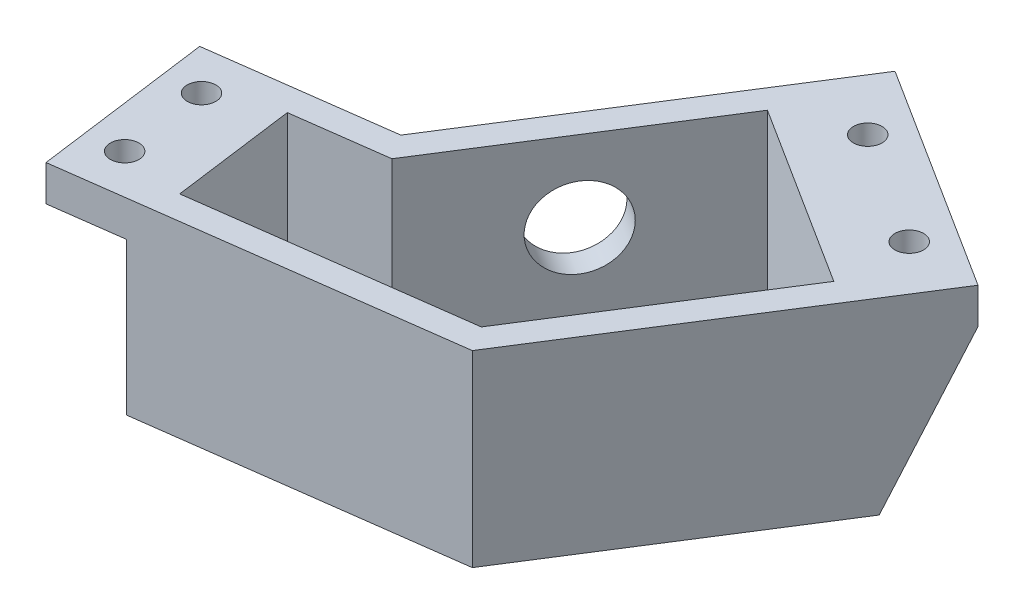
SolidWorks part; units mm, degrees
ref_plane "Спереди" through (0, 0, 0) normal (0, 0, 1) x (1, 0, 0)
ref_plane "Сверху" through (0, 0, 0) normal (0, 1, 0) x (1, 0, 0)
ref_plane "Справа" through (0, 0, 0) normal (1, 0, 0) x (0, 0, -1)
sketch "Sketch1" plane through (0, 0, 0) normal (0, 1, 0) x (1, 0, 0)
  line L0 (0, 0) -> (-19.8234, -2.6518)
  line L1 (-19.8234, -2.6518) -> (-17.1716, -22.4752)
  line L2 (-17.1716, -22.4752) -> (24.8344, -16.856)
  line L3 (24.8344, -16.856) -> (46.7569, 17.7141)
  line L4 (46.7569, 17.7141) -> (21.4217, 33.7803)
  line L5 (21.4217, 33.7803) -> (0, 0)
  line L6 (0, 0) -> (2.6518, -19.8234) construction
  dimension "D1" = 130
  dimension "D2" = 20
  dimension "D3" = 20
  dimension "D4" = 30
  dimension "D5" = 90
  dimension "D6" = 40
extrude "Boss-Extrude1" add sketch "Sketch1" along normal blind 21
sketch "Sketch2" plane through (0, 21, 0) normal (0, 1, 0) x (1, 0, 0)
  line L0 (21.4217, 33.7803) -> (17.1373, 27.0243)
  line L1 (21.4217, 33.7803) -> (0, 0) construction
  line L2 (17.1373, 27.0243) -> (42.4726, 10.958)
  line L3 (24.8344, -16.856) -> (46.7569, 17.7141) construction
  line L4 (42.4726, 10.958) -> (46.7569, 17.7141)
  line L5 (46.7569, 17.7141) -> (21.4217, 33.7803)
  line L6 (-19.8234, -2.6518) -> (-17.1716, -22.4752)
  line L7 (-17.1716, -22.4752) -> (-9.2422, -21.4145)
  line L8 (-17.1716, -22.4752) -> (24.8344, -16.856) construction
  line L9 (-9.2422, -21.4145) -> (-11.8941, -1.5911)
  line L10 (0, 0) -> (-19.8234, -2.6518) construction
  line L11 (-11.8941, -1.5911) -> (-19.8234, -2.6518)
  dimension "D1" = 8
extrude "Cut-Extrude1" cut sketch "Sketch2" along normal offset from surface (17 mm away) 4 from surface at -21 up to face at (9.3363, 21, -1.5852) starting at face at (9.3363, 0, -1.5852)
sketch "Sketch3" plane through (0, 21, 0) normal (0, 1, 0) x (1, 0, 0)
  line L0 (18.0642, 22.8841) -> (1.7843, -2.788)
  line L1 (1.7843, -2.788) -> (-8.5228, -4.1668)
  line L2 (-8.5228, -4.1668) -> (-6.6665, -18.0432)
  line L3 (-6.6665, -18.0432) -> (23.0501, -14.068)
  line L4 (23.0501, -14.068) -> (38.3324, 10.0311)
  line L5 (38.3324, 10.0311) -> (18.0642, 22.8841)
  line L6 (18.0642, 22.8841) -> (17.864, 23.073)
  line L7 (21.4217, 33.7803) -> (0, 0) construction
  line L9 (0, 0) -> (-19.8234, -2.6518) construction
  line L10 (-9.2422, -21.4145) -> (-11.8941, -1.5911) construction
  line L11 (-17.1716, -22.4752) -> (24.8344, -16.856) construction
  line L12 (24.8344, -16.856) -> (46.7569, 17.7141) construction
  line L13 (17.1373, 27.0243) -> (42.4726, 10.958) construction
  dimension "D1" = 3
  dimension "D2" = 3
  dimension "D3" = 3
  dimension "D4" = 3
  dimension "D5" = 3
  dimension "D6" = 3
extrude "Cut-Extrude2" cut sketch "Sketch3" against normal offset from surface (18 mm away) 3 contours L4 L5 L0 L1 L2 L3 up to face at (10.5514, 0, 0.3132)
sketch "Sketch4" plane through (2.5335, 0, 1.6066) normal (0.8445, 0, 0.5355) x (0.5355, 0, -0.8445)
  line L0 (13.8005, 3) -> (13.8005, 21) construction
  line L3 (29, 21) -> (-1.3989, 21) construction
  line L4 (3.3005, 4) -> (24.3005, 4) construction
  line L5 (3.3005, 4) -> (3.3005, 20) construction
  line L6 (3.3005, 20) -> (24.3005, 20) construction
  line L7 (24.3005, 4) -> (24.3005, 20) construction
  line L8 (3.3005, 4) -> (24.3005, 20) construction
  line L9 (3.3005, 20) -> (24.3005, 4) construction
  line L11 (29, 3) -> (-1.3989, 3) construction
  circle A0 centre (13.8005, 12) radius 4.5
  point P14 (13.8005, 21)
  dimension "D1" = 9
  dimension "D2" = 16
  dimension "D3" = 21
extrude "Cut-Extrude3" cut sketch "Sketch4" against normal through all
sketch "Sketch5" plane through (0, 17, 0) normal (0, -1, 0) x (-1, 0, 0)
  line L0 (-19.2795, 30.4023) -> (-44.6148, 14.3361) construction
  line L1 (-21.4217, 33.7803) -> (-17.1373, 27.0243) construction
  line L2 (-42.4726, 10.958) -> (-46.7569, 17.7141) construction
  line L3 (15.8587, -2.1215) -> (13.2069, -21.9449) construction
  line L4 (11.8941, -1.5911) -> (19.8234, -2.6518) construction
  line L5 (17.1716, -22.4752) -> (9.2422, -21.4145) construction
  line L8 (-21.4217, 33.7803) -> (-17.1373, 27.0243) construction
  circle A0 centre (-38.7032, 18.0848) radius 1.6
  circle A1 centre (-26.0356, 26.118) radius 1.6
  circle A2 centre (13.8699, -16.989) radius 1.6
  circle A3 centre (15.1958, -7.0773) radius 1.6
  point P20 (14.5328, -12.0332)
  dimension "D1" = 3.2
  dimension "D2" = 10
  dimension "D3" = 5
  dimension "D4" = 15
  dimension "D5" = 8
extrude "Cut-Extrude4" cut sketch "Sketch5" against normal through all
sketch "Sketch6" plane through (0, 0, 0) normal (-0.8445, 0, -0.5355) x (-0.5355, 0, 0.8445)
  line L0 (-24, 0) -> (-24, 21) construction
  line L1 (-32, 0) -> (0, 0) construction
  line L2 (-40, 21) -> (0, 21) construction
  line L3 (-32, 17) -> (-32, 0) construction
  text T0 "<b>      OBS</b>" font "Arial" height 3
  dimension "D1" = 8
extrude "Cut-Extrude5" cut sketch "Sketch6" against normal blind 0.5
sketch "Sketch7" plane through (-8.9205, 0, 1.1933) normal (0.9912, 0, -0.1326) x (-0.1326, 0, -0.9912)
  line L0 (-10, 3) -> (-10, 21) construction
  line L1 (-3, 3) -> (-17, 3) construction
  line L2 (-3, 21) -> (-17, 21) construction
  circle A0 centre (-10, 10) radius 3
  dimension "D1" = 6
  dimension "D2" = 11
extrude "Cut-Extrude6" cut sketch "Sketch7" against normal through all
sketch "Sketch8" plane through (0, 0, 0) normal (-0.8445, 0, -0.5355) x (-0.5355, 0, 0.8445)
  line L0 (-32, 0) -> (-40, 17)
  line L1 (-40, 17) -> (-32, 17)
  line L2 (-32, 17) -> (-32, 0)
extrude "Boss-Extrude2" add sketch "Sketch8" against normal up to surface (30 mm away) up to face at (38.0213, 12.6667, -3.9387)
sketch "Sketch9" plane through (0, 21, 0) normal (0, 1, 0) x (1, 0, 0)
  circle A0 centre (26.0356, 26.118) radius 1.6
  circle A1 centre (38.7032, 18.0848) radius 1.6
extrude "Cut-Extrude7" cut sketch "Sketch9" against normal through all
sketch "Sketch10" plane through (0, 21, 0) normal (0, 1, 0) x (1, 0, 0)
  circle A0 centre (26.0356, 26.118) radius 3.5
  circle A1 centre (38.7032, 18.0848) radius 3.5
  dimension "D1" = 7
extrude "Cut-Extrude8" cut sketch "Sketch10" against normal through all from offset 4 offset against normal yes
sketch "Sketch11" plane through (0, 0, 0) normal (-0.1326, 0, -0.9912) x (-0.9912, 0, 0.1326)
  line L0 (7, 0) -> (7, 21) construction
  line L1 (0, 0) -> (12, 0) construction
  line L2 (0, 21) -> (20, 21) construction
  line L3 (12, 17) -> (12, 0) construction
  text T0 "<b>     1 / 2</b>" font "Arial" height 3
  dimension "D1" = 5
extrude "Cut-Extrude9" cut sketch "Sketch11" against normal blind 0.5
